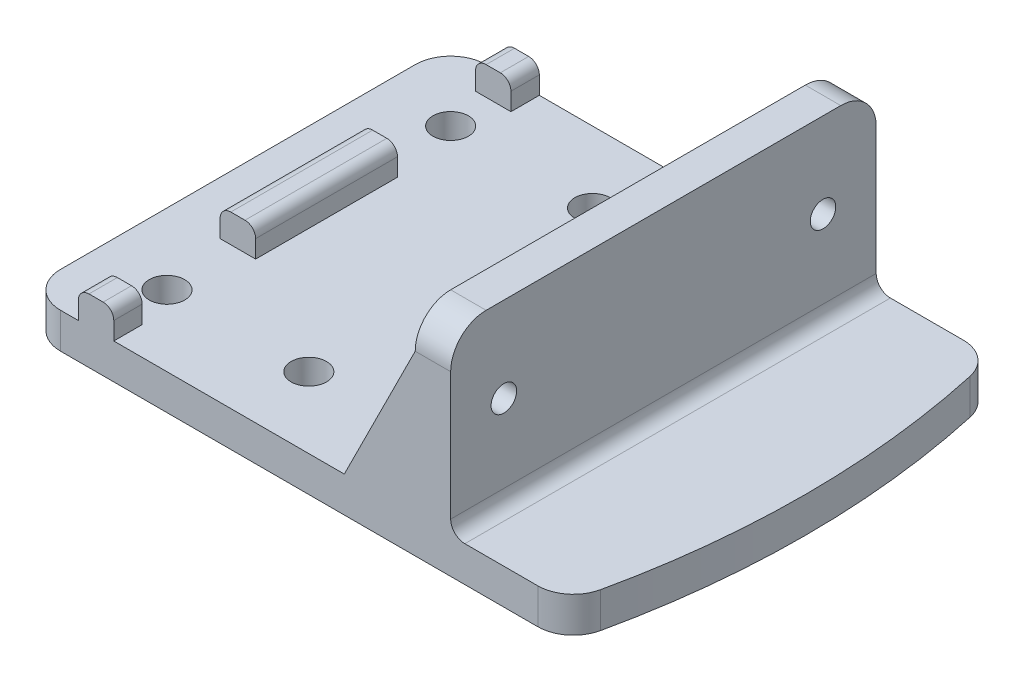
SolidWorks part; units mm, degrees
ref_plane "Front Plane" through (0, 0, 0) normal (0, 0, 1) x (1, 0, 0)
ref_plane "Top Plane" through (0, 0, 0) normal (0, 1, 0) x (1, 0, 0)
ref_plane "Right Plane" through (0, 0, 0) normal (1, 0, 0) x (0, 0, -1)
sketch "Sketch1" plane through (0, 0, 0) normal (0, 1, 0) x (1, 0, 0)
  line L1 (40, -30) -> (-40, -30)
  line L2 (40, -30) -> (40, 30)
  line L3 (40, 30) -> (-40, 30)
  line L4 (-40, -30) -> (-40, 30)
  line L5 (40, -30) -> (-40, 30) construction
  line L6 (40, 30) -> (-40, -30) construction
  point P0 (0, 0)
  dimension "D1" = 60
  dimension "D2" = 80
extrude "Boss-Extrude1" add sketch "Sketch1" along normal blind 5
sketch "Sketch2" plane through (0, 5, 0) normal (0, 1, 0) x (1, 0, 0)
  line L0 (40, 30) -> (-40, 30) construction
  line L1 (15, 30) -> (20, 30)
  line L2 (15, 30) -> (15, -30)
  line L3 (15, -30) -> (20, -30)
  line L4 (20, 30) -> (20, -30)
  line L5 (-40, -30) -> (40, -30) construction
  line L6 (40, -30) -> (40, 30) construction
  dimension "D1" = 5
  dimension "D2" = 60
  dimension "D3" = 20
extrude "Boss-Extrude2" add sketch "Sketch2" along normal blind 25
sketch "Sketch3" plane through (15, 0, 0) normal (-1, 0, 0) x (0, 0, 1)
  line L0 (-30, 5) -> (30, 5) construction
  line L1 (0, -16.5) -> (0, 16.5) construction
  circle A0 centre (-22.5, 18) radius 1.8
  circle A1 centre (22.5, 18) radius 1.8
  dimension "D1" = 22.5
  dimension "D2" = 13
extrude "Cut-Extrude1" cut sketch "Sketch3" against normal blind 30
sketch "Sketch5" plane through (0, 5, 0) normal (0, 1, 0) x (1, 0, 0)
  line L0 (40, 30) -> (20, 30) construction
  line L2 (36.2439, 30) -> (36.2439, 30.1406)
  line L3 (36.2439, 30.1406) -> (46.6259, 30.1406)
  line L4 (46.6259, 30) -> (46.6259, 30.1406)
  line L5 (46.6259, 30.1406) -> (46.6259, -29.7346)
  line L6 (36.2439, -30) -> (46.6259, -30)
  line L8 (20, -30) -> (40, -30) construction
  line L9 (46.6259, -30) -> (46.6259, -29.7346)
  circle A0 centre (-81.6847, 0) radius 121.6847
extrude "Cut-Extrude2" cut sketch "Sketch5" against normal blind 30 contours A0 L9 L5 L4 L3 L2
fillet "Fillet1" radius 5 6 edges at (-40, 2.5, 30) (-40, 2.5, -30) (36.2439, 2.5, -30) (36.2439, 2.5, 30) (17.5, 30, 30) (17.5, 30, -30)
sketch "Sketch6" plane through (0, 5, 0) normal (0, 1, 0) x (1, 0, 0)
  line L0 (-40, 25) -> (-40, -25) construction
  line L1 (-16.5, 0) -> (16.5, 0) construction
  circle A0 centre (-30, 20) radius 2.5
  circle A1 centre (-30, -20) radius 2.5
  circle A2 centre (-10, 20) radius 2.5
  circle A3 centre (-10, -20) radius 2.5
  dimension "D1" = 10
  dimension "D2" = 20
  dimension "D4" = 20
  dimension "D3" = 2
extrude "Cut-Extrude3" cut sketch "Sketch6" against normal blind 30
sketch "Sketch8" plane through (0, 5, 0) normal (0, 1, 0) x (1, 0, 0)
  line L0 (15, 30) -> (-35, 30) construction
  line L1 (-27.5, -10) -> (-32.5, -10)
  line L2 (-27.5, -10) -> (-27.5, 10)
  line L3 (-27.5, 10) -> (-32.5, 10)
  line L4 (-32.5, -10) -> (-32.5, 10)
  line L5 (-27.5, -10) -> (-32.5, 10) construction
  line L6 (-27.5, 10) -> (-32.5, -10) construction
  line L7 (-27.5, 30) -> (-32.5, 30)
  line L8 (-27.5, 30) -> (-27.5, 26)
  line L9 (-27.5, 26) -> (-32.5, 26)
  line L10 (-32.5, 30) -> (-32.5, 26)
  line L11 (-16.5, 0) -> (16.5, 0) construction
  line L12 (-32.5, -30) -> (-32.5, -26)
  line L13 (-27.5, -26) -> (-32.5, -26)
  line L14 (-27.5, -30) -> (-27.5, -26)
  line L15 (-27.5, -30) -> (-32.5, -30)
  circle A0 centre (-30, 20) radius 2.5 construction
  point P0 (-30, 0)
  dimension "D1" = 5
  dimension "D2" = 0
  dimension "D3" = 20
  dimension "D4" = 4
extrude "Boss-Extrude3" add sketch "Sketch8" along normal blind 4
fillet "Fillet3" radius 1.5 6 edges at (-27.5, 9, 28) (-32.5, 9, 28) (-27.5, 9, 0) (-32.5, 9, 0) (-27.5, 9, -28) (-32.5, 9, -28)
sketch "Sketch9" plane through (0, 0, 30) normal (0, 0, 1) x (1, 0, 0)
  line L0 (15, 25) -> (5, 5)
  line L1 (-27.5, 5) -> (15, 5) construction
  line L2 (5, 5) -> (15, 5)
  line L3 (15, 5) -> (15, 25)
  dimension "D1" = 10
extrude "Boss-Extrude4" add sketch "Sketch9" against normal blind 3
mirror "Mirror1" about plane through (0, 0, 0) normal (0, 0, 1) of "Boss-Extrude4"
fillet "Fillet4" radius 5 1 edges at (15, 5, 0)
fillet "Fillet5" radius 2 1 edges at (20, 5, 0)
